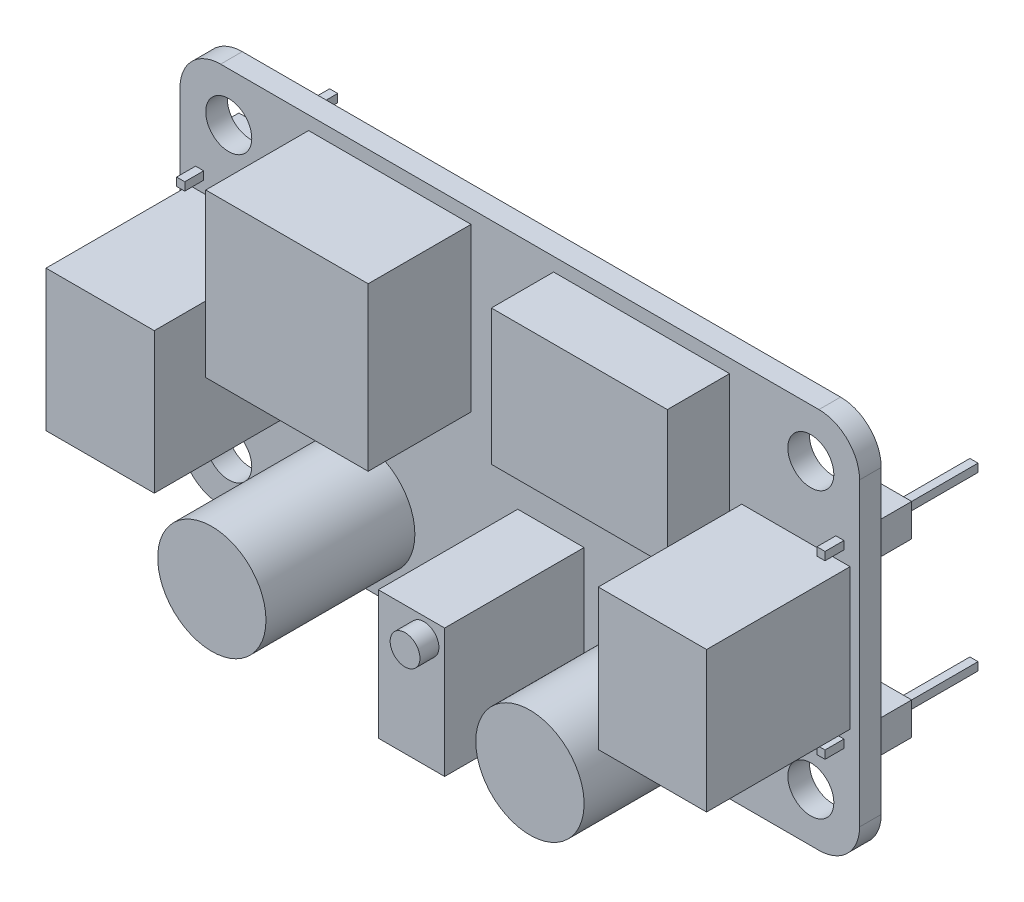
SolidWorks part; units mm, degrees
ref_plane "Plan de face" through (0, 0, 0) normal (0, 0, 1) x (1, 0, 0)
ref_plane "Plan de dessus" through (0, 0, 0) normal (0, 1, 0) x (1, 0, 0)
ref_plane "Plan de droite" through (0, 0, 0) normal (1, 0, 0) x (0, 0, -1)
sketch "Esquisse1" plane through (0, 0, 0) normal (0, 0, 1) x (1, 0, 0)
  line L1 (-25.1, 14.1) -> (25.1, 14.1)
  line L2 (-25.1, 14.1) -> (-25.1, -14.1)
  line L3 (-25.1, -14.1) -> (25.1, -14.1)
  line L4 (25.1, 14.1) -> (25.1, -14.1)
  point P4 (0, 14.1)
  point P6 (-25.1, 0)
  dimension "D1" = 50.2
  dimension "D2" = 28.2
extrude "Boss.-Extru.1" add sketch "Esquisse1" along normal blind 1.6
hole_wizard "Dégagement M31" positions "Esquisse3" profile "Esquisse4" hole size "M3" standard "ISO" end condition through all
sketch "Esquisse3" plane through (0, 0, 1.6) normal (0, 0, 1) x (1, 0, 0)
  line L0 (0, 0) -> (0, 5.8427) construction
  line L2 (0, 0) -> (4.0489, 0) construction
  point P0 (-21.5, 10.5)
  point P12 (21.5, 10.5)
  point P13 (21.5, -10.5)
  point P14 (-21.5, -10.5)
  dimension "D1" = 21
  dimension "D2" = 43
sketch "Esquisse4" plane through (-21.5, 10.5, 1.6) normal (1, 0, 0) x (0, -1, 0)
  line L0 (0, 0) -> (0, 1.6)
  line L1 (0, 1.6) -> (1.7, 1.6)
  line L2 (1.7, 1.6) -> (1.7, 0)
  line L5 (1.7, 0) -> (0, 0)
  line L11 (0, -6.35) -> (0, 107.95) construction
  dimension "Diamètre du perçage jusqu'au prochain" = 3.4
  dimension "Profondeur du perçage jusqu'au prochain" = 1.6
fillet "Congé1" radius 3 4 edges at (-25.1, 14.1, 0.8) (25.1, 14.1, 0.8) (25.1, -14.1, 0.8) (-25.1, -14.1, 0.8)
sketch "Esquisse5" plane through (0, 0, 1.6) normal (0, 0, 1) x (1, 0, 0)
  line L0 (0, 0) -> (0, 5.9405) construction
  line L1 (-24.4, 5.2) -> (-16.4, 5.2)
  line L2 (-24.4, 5.2) -> (-24.4, -5.2)
  line L3 (-24.4, -5.2) -> (-16.4, -5.2)
  line L4 (-16.4, 5.2) -> (-16.4, -5.2)
  line L13 (16.4, 5.2) -> (16.4, -5.2)
  line L22 (24.4, -5.2) -> (16.4, -5.2)
  line L23 (24.4, 5.2) -> (24.4, -5.2)
  line L24 (24.4, 5.2) -> (16.4, 5.2)
  line L25 (-25.1, 11.1) -> (-25.1, -11.1) construction
  point P4 (-16.4, 0)
  dimension "D1" = 10.4
  dimension "D2" = 8
  dimension "D3" = 0.7
extrude "Boss.-Extru.2" add sketch "Esquisse5" along normal blind 10.6
sketch "Esquisse6" plane through (0, 0, 1.6) normal (0, 0, 1) x (1, 0, 0)
  line L0 (0, 0) -> (0, 3.5127) construction
  line L1 (-22.1, -14.1) -> (22.1, -14.1) construction
  circle A0 centre (-11.75, -8.8) radius 4
  circle A1 centre (11.75, -8.8) radius 4
  point P7 (-11.75, -12.8)
  dimension "D1" = 8
  dimension "D2" = 23.5
  dimension "D3" = 1.3
extrude "Boss.-Extru.3" add sketch "Esquisse6" along normal blind 11 separate body
sketch "Esquisse7" plane through (0, 0, 1.6) normal (0, 0, 1) x (1, 0, 0)
  line L0 (-22.1, -14.1) -> (22.1, -14.1) construction
  line L1 (-0.15, -3.4) -> (4.75, -3.4)
  line L2 (-0.15, -3.4) -> (-0.15, -12.9)
  line L3 (-0.15, -12.9) -> (4.75, -12.9)
  line L4 (4.75, -3.4) -> (4.75, -12.9)
  circle A0 centre (11.75, -8.8) radius 4 construction
  point P6 (7.75, -8.8)
  dimension "D1" = 4.9
  dimension "D2" = 9.5
  dimension "D3" = 1.2
  dimension "D4" = 3
extrude "Boss.-Extru.4" add sketch "Esquisse7" along normal blind 10.3 separate body
sketch "Esquisse8" plane through (0, 0, 11.9) normal (0, 0, 1) x (1, 0, 0)
  circle A0 centre (3.2234, -4.8554) radius 1.1
  dimension "D1" = 2.2
extrude "Boss.-Extru.5" add sketch "Esquisse8" along normal blind 1.4
sketch "Esquisse9" plane through (0, 0, 1.6) normal (0, 0, 1) x (1, 0, 0)
  line L0 (22.1, 14.1) -> (-22.1, 14.1) construction
  line L1 (-15.6, 13.1) -> (-3.6, 13.1)
  line L2 (-15.6, 13.1) -> (-15.6, 1.1)
  line L3 (-15.6, 1.1) -> (-3.6, 1.1)
  line L4 (-3.6, 13.1) -> (-3.6, 1.1)
  line L5 (-25.1, 11.1) -> (-25.1, -11.1) construction
  dimension "D1" = 12
  dimension "D2" = 1
  dimension "D3" = 9.5
extrude "Boss.-Extru.6" add sketch "Esquisse9" along normal blind 7.6 separate body
sketch "Esquisse10" plane through (0, 0, 1.6) normal (0, 0, 1) x (1, 0, 0)
  line L0 (22.1, 14.1) -> (-22.1, 14.1) construction
  line L1 (2.5, 13.1) -> (15.5, 13.1)
  line L2 (2.5, 13.1) -> (2.5, 3.1)
  line L3 (2.5, 3.1) -> (15.5, 3.1)
  line L4 (15.5, 13.1) -> (15.5, 3.1)
  line L5 (25.1, -11.1) -> (25.1, 11.1) construction
  dimension "D1" = 10
  dimension "D2" = 13
  dimension "D3" = 1
  dimension "D4" = 9.6
extrude "Boss.-Extru.7" add sketch "Esquisse10" along normal blind 4.6 separate body
sketch "Esquisse11" plane through (0, 0, 0) normal (0, 0, -1) x (-1, 0, 0)
  line L1 (-23.95, 6.65) -> (-23.35, 6.65)
  line L2 (-23.95, 6.65) -> (-23.95, 6.05)
  line L3 (-23.95, 6.05) -> (-23.35, 6.05)
  line L4 (-23.35, 6.65) -> (-23.35, 6.05)
  line L5 (0, 0) -> (0, 3.2731) construction
  line L6 (0, 0) -> (2.3827, 0) construction
  line L7 (23.35, 6.65) -> (23.35, 6.05)
  line L8 (23.95, 6.05) -> (23.35, 6.05)
  line L9 (23.95, 6.65) -> (23.95, 6.05)
  line L10 (23.95, 6.65) -> (23.35, 6.65)
  line L11 (-23.35, -6.65) -> (-23.35, -6.05)
  line L12 (-23.95, -6.05) -> (-23.35, -6.05)
  line L13 (-23.95, -6.65) -> (-23.95, -6.05)
  line L14 (-23.95, -6.65) -> (-23.35, -6.65)
  line L15 (23.95, -6.65) -> (23.35, -6.65)
  line L16 (23.95, -6.65) -> (23.95, -6.05)
  line L17 (23.95, -6.05) -> (23.35, -6.05)
  line L18 (23.35, -6.65) -> (23.35, -6.05)
  point P20 (-23.95, 6.35)
  point P21 (-23.95, -6.35)
  point P22 (-23.2158, 6.2)
  point P23 (-23.65, 6.65)
  point P24 (23.65, 6.65)
  dimension "D1" = 0.6
  dimension "D2" = 12.7
  dimension "D3" = 47.3
extrude "Boss.-Extru.8" add sketch "Esquisse11" along normal blind 8.3 and the other way blind 3 separate body
sketch "Esquisse12" plane through (0, 0, 0) normal (0, 0, -1) x (-1, 0, 0)
  line L1 (-24.85, 7.55) -> (-22.45, 7.55)
  line L2 (-24.85, 7.55) -> (-24.85, 5.15)
  line L3 (-24.85, 5.15) -> (-22.45, 5.15)
  line L4 (-22.45, 7.55) -> (-22.45, 5.15)
  line L5 (-23.35, 6.65) -> (-23.95, 6.65) construction
  line L6 (-23.35, 6.05) -> (-23.35, 6.65) construction
  line L7 (0, 0) -> (0, 3.362) construction
  line L8 (0, 0) -> (1.9873, 0) construction
  line L9 (22.45, 7.55) -> (22.45, 5.15)
  line L10 (24.85, 5.15) -> (22.45, 5.15)
  line L11 (24.85, 7.55) -> (24.85, 5.15)
  line L12 (24.85, 7.55) -> (22.45, 7.55)
  line L13 (24.85, -7.55) -> (22.45, -7.55)
  line L14 (24.85, -7.55) -> (24.85, -5.15)
  line L15 (24.85, -5.15) -> (22.45, -5.15)
  line L16 (22.45, -7.55) -> (22.45, -5.15)
  line L17 (-22.45, -7.55) -> (-22.45, -5.15)
  line L18 (-24.85, -5.15) -> (-22.45, -5.15)
  line L19 (-24.85, -7.55) -> (-24.85, -5.15)
  line L20 (-24.85, -7.55) -> (-22.45, -7.55)
  point P8 (-23.65, 6.65)
  point P9 (-23.65, 7.55)
  point P11 (-23.35, 6.35)
  point P12 (-22.45, 6.35)
  dimension "D1" = 2.4
extrude "Boss.-Extru.9" add sketch "Esquisse12" along normal blind 2.5 separate body
